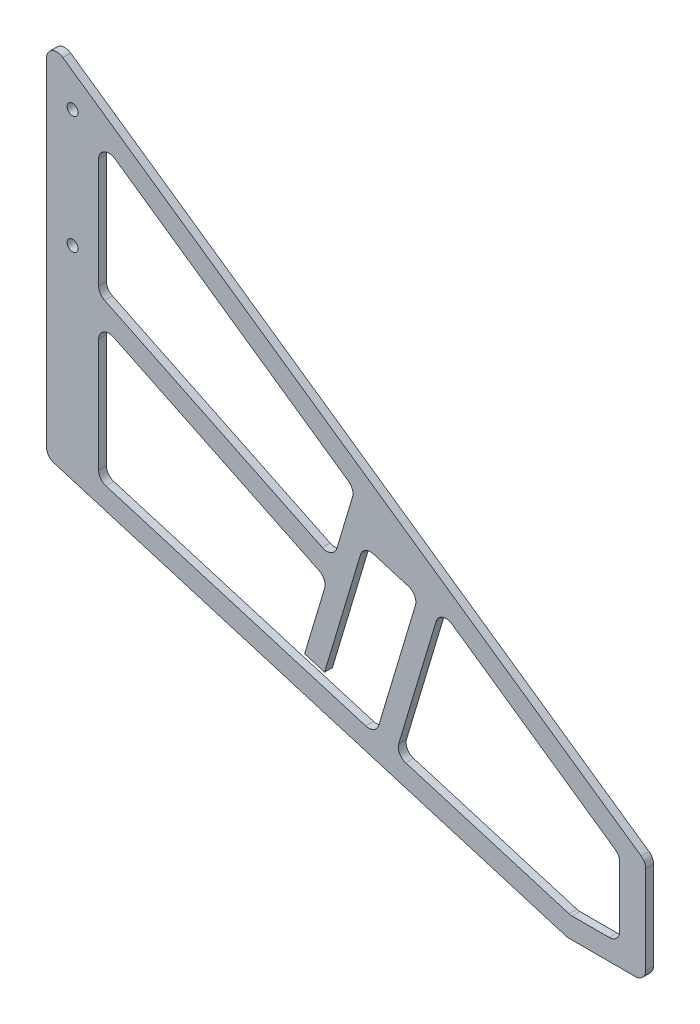
SolidWorks part; units mm, degrees
ref_plane "Спереди" through (0, 0, 0) normal (0, 0, 1) x (1, 0, 0)
ref_plane "Сверху" through (0, 0, 0) normal (0, 1, 0) x (1, 0, 0)
ref_plane "Справа" through (0, 0, 0) normal (1, 0, 0) x (0, 0, -1)
sketch "Эскиз1" plane through (0, 0, 0) normal (0, 0, 1) x (1, 0, 0)
  line L5 (0, 0) -> (0, 140)
  line L10 (0, 140) -> (230, -20)
  line L11 (230, -20) -> (230, -60)
  line L12 (230, -60) -> (200, -60)
  line L13 (200, -60) -> (0, 0)
  dimension "D1" = 230
  dimension "D2" = 40
  dimension "D3" = 30
  dimension "D4" = 140
  dimension "D5" = 60
extrude "Бобышка-Вытянуть1" add sketch "Эскиз1" along normal blind 3
sketch "Эскиз2" plane through (0, 0, 3) normal (0, 0, 1) x (1, 0, 0)
  line L0 (0, 140) -> (0, 0) construction
  circle A0 centre (10, 75) radius 2.1
  circle A1 centre (10, 120.2) radius 2.1
  dimension "D1" = 4.2
  dimension "D2" = 75
  dimension "D3" = 10
  dimension "D4" = 4.2
  dimension "D5" = 45.2
  dimension "D6" = 10
extrude "Вырез-Вытянуть1" cut sketch "Эскиз2" against normal blind 39
sketch "Эскиз5" plane through (0, 0, 3) normal (0, 0, 1) x (1, 0, 0)
  line L0 (220, -19.1343) -> (220, -55)
  line L1 (230, -60) -> (230, -20) construction
  line L5 (20, 119.9961) -> (20, -0.7798)
  line L6 (0, 140) -> (0, 0) construction
  line L10 (5, 3.7202) -> (200.7338, -55)
  line L11 (200.7338, -55) -> (225, -55)
  line L12 (225, -55) -> (225, -22.6126)
  line L13 (225, -22.6126) -> (5, 130.4309)
  line L14 (5, 130.4309) -> (5, 3.7202)
  line L15 (20, -0.7798) -> (200.7338, -55)
  line L16 (200.7338, -55) -> (220, -55)
  line L18 (220, -19.1343) -> (20, 119.9961)
  dimension "D2" = 20
  dimension "D3" = 10
  dimension "D1" = 5
extrude "Вырез-Вытянуть2" cut sketch "Эскиз5" against normal blind 10
sketch "Эскиз6" plane through (0, 0, 0) normal (0, 0, 1) x (1, 0, 0)
  line L1 (200.7338, -55) -> (220, -55) construction
  line L2 (20, -0.7798) -> (200.7338, -55) construction
  line L3 (20, 119.9961) -> (20, -0.7798) construction
  line L4 (220, -19.1343) -> (20, 119.9961) construction
  line L5 (220, -55) -> (220, -19.1343)
  line L6 (200.7338, -55) -> (220, -55)
  line L7 (20, -0.7798) -> (200.7338, -55)
  line L8 (20, 119.9961) -> (20, -0.7798)
  line L9 (220, -19.1343) -> (20, 119.9961)
  line L10 (178.4118, 9.7966) -> (178.4118, -48.3034) construction
  line L11 (171.4118, -46.2034) -> (220, -46.2034)
  line L13 (171.4118, -18.2034) -> (171.4118, -46.2034)
  line L14 (185.1618, -18.2034) -> (185.1618, -46.2034)
  line L15 (171.4118, -18.2034) -> (174.4118, -18.2034)
  line L16 (174.4118, -18.2034) -> (174.4118, 12.5792)
  line L17 (182.4118, -18.2034) -> (182.4118, 7.014)
  line L18 (182.4118, -18.2034) -> (185.1618, -18.2034)
  dimension "D1" = 28
  dimension "D2" = 4
  dimension "D3" = 6.75
  dimension "D4" = 8
  dimension "D5" = 3
  dimension "D6" = 28
sketch "Эскиз7" plane through (0, 0, 0) normal (0, 0, 1) x (1, 0, 0)
  line L0 (114.9827, -29.2747) -> (135.632, 39.5564) construction
  line L11 (20, -0.7798) -> (200.7338, -55) construction
  line L16 (220, -19.1343) -> (20, 119.9961) construction
  line L17 (105.3087, -23.2404) -> (126.3808, -29.562)
  line L18 (126.3808, -29.562) -> (142.7597, 25.0341)
  line L19 (142.7597, 25.0341) -> (121.6875, 31.3557)
  line L20 (121.6875, 31.3557) -> (106.7454, -18.4512)
  line L25 (97.646, -20.9416) -> (20, 2.3522)
  line L26 (20, 119.9961) -> (20, -0.7798) construction
  line L27 (134.0434, -31.8608) -> (201.1742, -52)
  line L28 (200.7338, -55) -> (220, -55) construction
  line L29 (20, 116.3416) -> (118.3134, 47.9497)
  line L31 (20, 59.6081) -> (220, -37.0672) construction
  line L32 (151.1365, 25.1162) -> (220.1765, -22.9116)
  line L33 (230, -20) -> (0, 140) construction
  line L34 (134.0434, -31.8608) -> (151.1365, 25.1162)
  line L35 (134.0434, -31.8608) -> (152.7211, 30.3979) construction
  line L36 (118.3134, 47.9497) -> (110.0809, 20.5079)
  line L37 (116.3237, 41.3171) -> (97.646, -20.9416) construction
  line L39 (152.7211, 30.3979) -> (116.3237, 41.3171) construction
  line L41 (20, -0.7798) -> (200.7338, -55)
  line L44 (20, -0.7798) -> (20, 2.3522)
  line L46 (220.1765, -13.1662) -> (20, 126.087)
  line L47 (20, 116.3416) -> (20, 126.087)
  line L48 (220.1765, -22.9116) -> (220.1765, -13.1662)
  line L49 (20, 64.0509) -> (110.0809, 20.5079)
  line L50 (20, 55.1653) -> (107.7528, 12.7477)
  line L51 (220, -52) -> (220, -55)
  line L52 (99.0828, -16.1524) -> (106.7454, -18.4512)
  line L53 (97.646, -20.9416) -> (105.3087, -23.2404)
  line L54 (121.6875, 31.3557) -> (105.3087, -23.2404) construction
  line L55 (107.7528, 12.7477) -> (99.0828, -16.1524)
  line L56 (20, 64.0509) -> (20, 55.1653)
  line L57 (201.1742, -52) -> (220, -52)
  line L59 (220, -55) -> (200.7338, -55)
  point P15 (0, 0)
  point P34 (0, 0)
  point P35 (0, 0)
  point P38 (0, 0)
  point P39 (0, 0)
  point P40 (0, 0)
  point P44 (0, 0)
  point P45 (0, 0)
  dimension "D1" = 22
  dimension "D2" = 11
  dimension "D3" = 57
  dimension "D4" = 3
  dimension "D6" = 3
  dimension "D7" = 3
  dimension "D8" = 4
  dimension "D9" = 4
  dimension "D10" = 5
  dimension "D11" = 3
  dimension "D5" = 8
extrude "Бобышка-Вытянуть4" add sketch "Эскиз7" along normal blind 3
fillet "Скругление1" radius 4 5 edges at (0, 0, 1.5) (0, 140, 1.5) (200, -60, 1.5) (230, -60, 1.5) (230, -20, 1.5)
fillet "Скругление2" radius 4 15 edges at (201.1742, -52, 1.5) (220, -52, 1.5) (220, -22.7888, 1.5) (151.1365, 25.1162, 1.5) (121.6875, 31.3557, 1.5) (142.7597, 25.0341, 1.5) (126.3808, -29.562, 1.5) (134.0434, -31.8608, 1.5) (20, 2.3522, 1.5) (20, 55.1653, 1.5) (107.7528, 12.7477, 1.5) (110.0809, 20.5079, 1.5) (118.3134, 47.9497, 1.5) (20, 116.3416, 1.5) (20, 64.0509, 1.5)
equation "\"13б5\"=20.1238"
